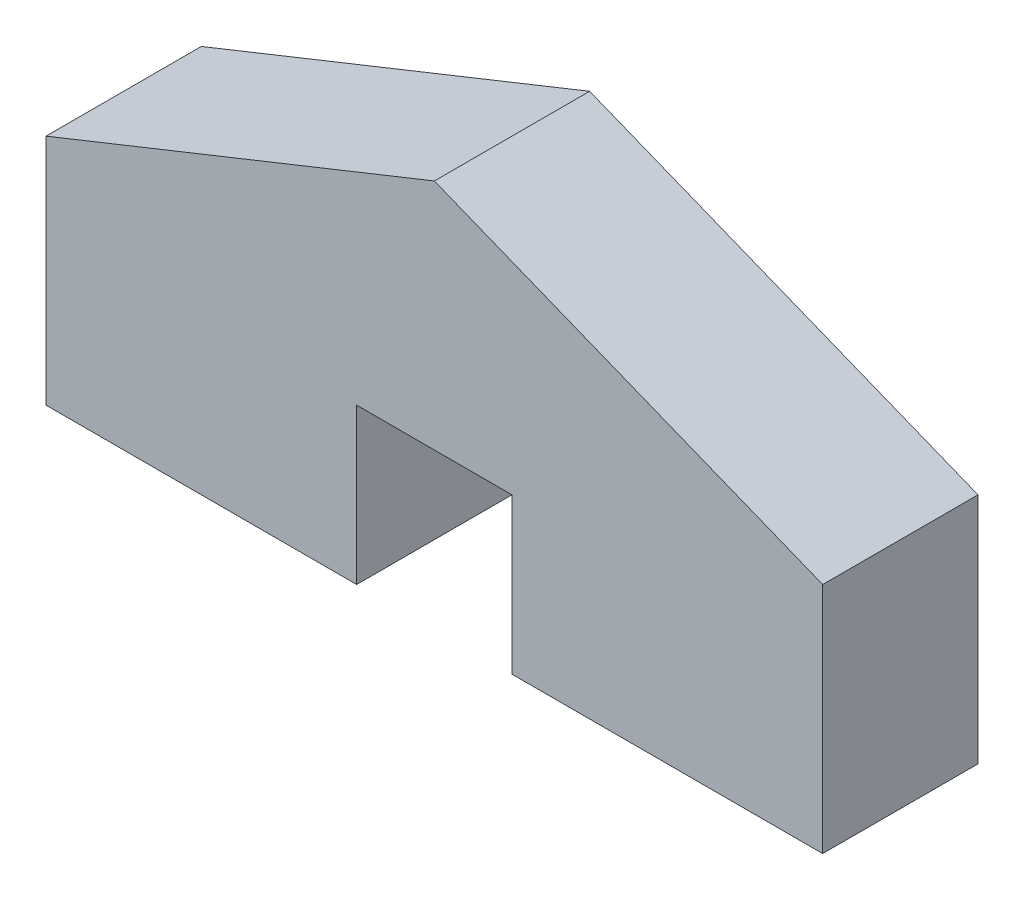
SolidWorks part; units mm, degrees
ref_plane "Front Plane" through (0, 0, 0) normal (0, 0, 1) x (1, 0, 0)
ref_plane "Top Plane" through (0, 0, 0) normal (0, 1, 0) x (1, 0, 0)
ref_plane "Right Plane" through (0, 0, 0) normal (1, 0, 0) x (0, 0, -1)
sketch "Sketch1" plane through (0, 0, 0) normal (0, 0, 1) x (1, 0, 0)
  line L0 (50, 0) -> (-50, 0)
  line L1 (-50, 0) -> (-50, 30)
  line L2 (50, 0) -> (50, 30)
  line L3 (-50, 30) -> (0, 50)
  line L4 (0, 50) -> (50, 30)
  point P4 (0, 0)
  point P8 (-50, 0)
  dimension "D1" = 30
  dimension "D2" = 100
  dimension "D3" = 50
extrude "Boss-Extrude1" add sketch "Sketch1" along normal blind 20
sketch "Sketch2" plane through (0, 0, 20) normal (0, 0, 1) x (1, 0, 0)
  line L0 (-50, 0) -> (50, 0) construction
  line L1 (-10, 0) -> (10, 0)
  line L2 (-10, 0) -> (-10, 20)
  line L3 (-10, 20) -> (10, 20)
  line L4 (10, 0) -> (10, 20)
  line L5 (-50, 30) -> (-50, 0) construction
  dimension "D1" = 40
  dimension "D2" = 20
  dimension "D3" = 20
extrude "Cut-Extrude1" cut sketch "Sketch2" against normal through all
